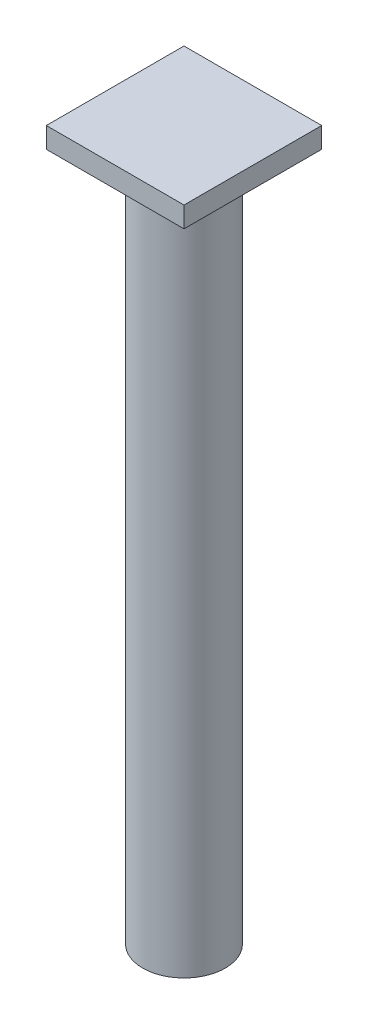
SolidWorks part; units mm, degrees
ref_plane "Front Plane" through (0, 0, 0) normal (0, 0, 1) x (1, 0, 0)
ref_plane "Top Plane" through (0, 0, 0) normal (0, 1, 0) x (1, 0, 0)
ref_plane "Right Plane" through (0, 0, 0) normal (1, 0, 0) x (0, 0, -1)
sketch "Sketch1" plane through (0, 0, 0) normal (0, 1, 0) x (1, 0, 0)
  circle A0 centre (0, 0) radius 30
  dimension "D1" = 60
extrude "Boss-Extrude1" add sketch "Sketch1" along normal blind 500
sketch "Sketch2" plane through (0, 0, 0) normal (0, -1, 0) x (-1, 0, 0)
  circle A0 centre (0, 0) radius 25
  dimension "D1" = 50
extrude "Cut-Extrude1" cut sketch "Sketch2" against normal blind 100
sketch "Sketch3" plane through (0, 500, 0) normal (0, 1, 0) x (1, 0, 0)
  line L1 (50, 50) -> (-50, 50)
  line L2 (50, 50) -> (50, -50)
  line L3 (50, -50) -> (-50, -50)
  line L4 (-50, 50) -> (-50, -50)
  point P4 (0, 50)
  point P6 (0, -50)
  point P7 (50, 0)
  point P8 (-50, 0)
  dimension "D1" = 100
  dimension "D2" = 100
extrude "Boss-Extrude2" add sketch "Sketch3" along normal blind 15
